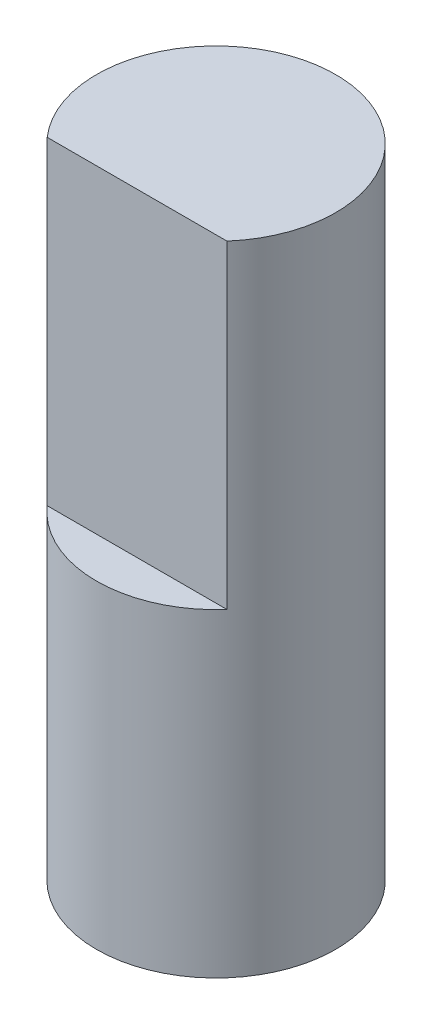
SolidWorks part; units mm, degrees
ref_plane "Front Plane" through (0, 0, 0) normal (0, 0, 1) x (1, 0, 0)
ref_plane "Top Plane" through (0, 0, 0) normal (0, 1, 0) x (1, 0, 0)
ref_plane "Right Plane" through (0, 0, 0) normal (1, 0, 0) x (0, 0, -1)
sketch "Sketch1" plane through (0, 0, 0) normal (0, 1, 0) x (1, 0, 0)
  circle A0 centre (0, 0) radius 1.5
  dimension "D1" = 3
extrude "Boss-Extrude1" add sketch "Sketch1" along normal blind 8
sketch "Sketch2" plane through (0, 8, 0) normal (0, 1, 0) x (1, 0, 0)
  line L0 (-1.1264, -0.9905) -> (1.1264, -0.9905)
  circle A0 centre (0, 0) radius 1.5 construction
  arc A1 (-1.1264, -0.9905) -> (1.1264, -0.9905) centre (0, 0) ccw
extrude "Cut-Extrude1" cut sketch "Sketch2" against normal blind 4
